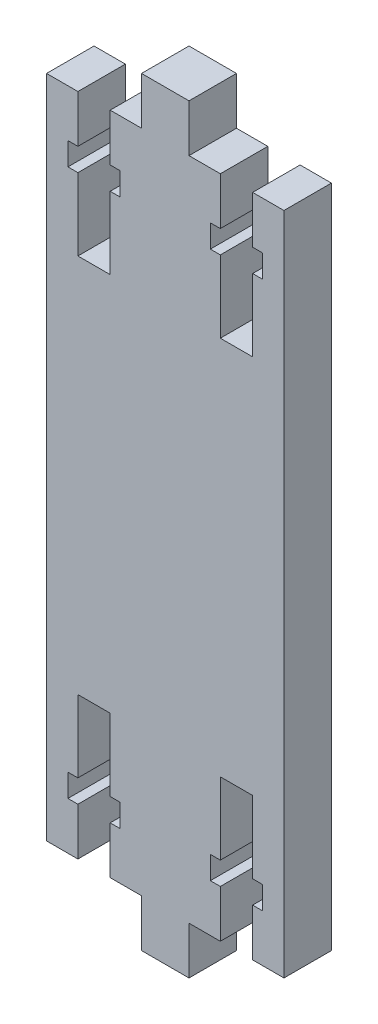
SolidWorks part; units mm, degrees
ref_plane "Front Plane" through (0, 0, 0) normal (0, 0, 1) x (1, 0, 0)
ref_plane "Top Plane" through (0, 0, 0) normal (0, 1, 0) x (1, 0, 0)
ref_plane "Right Plane" through (0, 0, 0) normal (1, 0, 0) x (0, 0, -1)
sketch "Sketch1" plane through (0, 0, 0) normal (0, 0, 1) x (1, 0, 0)
  line L8 (0, 0) -> (-15.7959, 0) construction
  line L15 (-12.5, 35) -> (-12.5, -35)
  line L16 (-12.5, -35) -> (-2.5, -35)
  line L17 (-2.5, -35) -> (-2.5, -40)
  line L18 (-2.5, -40) -> (2.5, -40)
  line L19 (2.5, -40) -> (2.5, -35)
  line L20 (2.5, -35) -> (12.5, -35)
  line L21 (12.5, -35) -> (12.5, 35)
  line L22 (2.5, 35) -> (12.5, 35)
  line L23 (2.5, 40) -> (2.5, 35)
  line L24 (-2.5, 40) -> (2.5, 40)
  line L25 (-2.5, 35) -> (-2.5, 40)
  line L26 (-12.5, 35) -> (-2.5, 35)
  point P8 (12.5, 0)
  point P13 (12.5, 0)
  point P18 (-7.5, 0)
  point P19 (-12.5, 0)
  dimension "D5" = 12.5
  dimension "D6" = 25
  dimension "D1" = 70
  dimension "D2" = 5
  dimension "D3" = 5
  dimension "D4" = 10
extrude "Boss-Extrude1" add sketch "Sketch1" along normal blind 5
sketch "Sketch2" plane through (0, 0, 0) normal (0, 0, -1) x (-1, 0, 0)
  line L0 (0, 0) -> (0, 29.5356) construction
  line L1 (0, 0) -> (21.6986, 0) construction
  line L2 (7.5, 35) -> (7.5, 31.1748) construction
  line L3 (2.5, 35) -> (12.5, 35) construction
  line L4 (5.8, 35) -> (9.2, 35)
  line L5 (9.2, 35) -> (9.2, 30)
  line L6 (9.2, 30) -> (10.25, 30)
  line L7 (10.25, 30) -> (10.25, 27.6)
  line L8 (10.25, 27.6) -> (9.2, 27.6)
  line L9 (9.2, 27.6) -> (9.2, 20)
  line L10 (9.2, 20) -> (5.8, 20)
  line L11 (5.8, 27.6) -> (5.8, 20)
  line L12 (4.75, 27.6) -> (5.8, 27.6)
  line L13 (4.75, 30) -> (4.75, 27.6)
  line L14 (5.8, 30) -> (4.75, 30)
  line L15 (5.8, 35) -> (5.8, 30)
  line L16 (-7.5, 35) -> (-7.5, 31.1748) construction
  line L17 (-5.8, 35) -> (-5.8, 30)
  line L18 (-5.8, 30) -> (-4.75, 30)
  line L19 (-4.75, 30) -> (-4.75, 27.6)
  line L20 (-4.75, 27.6) -> (-5.8, 27.6)
  line L21 (-5.8, 27.6) -> (-5.8, 20)
  line L22 (-9.2, 20) -> (-5.8, 20)
  line L23 (-9.2, 27.6) -> (-9.2, 20)
  line L24 (-10.25, 27.6) -> (-9.2, 27.6)
  line L25 (-10.25, 30) -> (-10.25, 27.6)
  line L26 (-9.2, 30) -> (-10.25, 30)
  line L27 (-9.2, 35) -> (-9.2, 30)
  line L28 (-5.8, 35) -> (-9.2, 35)
  line L29 (-7.5, -35) -> (-7.5, -31.1748) construction
  line L30 (7.5, -35) -> (7.5, -31.1748) construction
  line L31 (-5.8, -35) -> (-9.2, -35)
  line L32 (-9.2, -35) -> (-9.2, -30)
  line L33 (-9.2, -30) -> (-10.25, -30)
  line L34 (-10.25, -30) -> (-10.25, -27.6)
  line L35 (-10.25, -27.6) -> (-9.2, -27.6)
  line L36 (-9.2, -27.6) -> (-9.2, -20)
  line L37 (-9.2, -20) -> (-5.8, -20)
  line L38 (-5.8, -27.6) -> (-5.8, -20)
  line L39 (-4.75, -27.6) -> (-5.8, -27.6)
  line L40 (-4.75, -30) -> (-4.75, -27.6)
  line L41 (-5.8, -30) -> (-4.75, -30)
  line L42 (-5.8, -35) -> (-5.8, -30)
  line L43 (5.8, -35) -> (5.8, -30)
  line L44 (5.8, -30) -> (4.75, -30)
  line L45 (4.75, -30) -> (4.75, -27.6)
  line L46 (4.75, -27.6) -> (5.8, -27.6)
  line L47 (5.8, -27.6) -> (5.8, -20)
  line L48 (9.2, -20) -> (5.8, -20)
  line L49 (9.2, -27.6) -> (9.2, -20)
  line L50 (10.25, -27.6) -> (9.2, -27.6)
  line L51 (10.25, -30) -> (10.25, -27.6)
  line L52 (9.2, -30) -> (10.25, -30)
  line L53 (9.2, -35) -> (9.2, -30)
  line L54 (5.8, -35) -> (9.2, -35)
  point P17 (7.5, 20)
  point P36 (-7.5, 20)
  point P65 (-7.5, -20)
  point P66 (7.5, -20)
  dimension "D1" = 5
  dimension "D2" = 2.4
  dimension "D3" = 1.7
  dimension "D4" = 2.75
  dimension "D5" = 15
extrude "Cut-Extrude1" cut sketch "Sketch2" against normal blind 10
